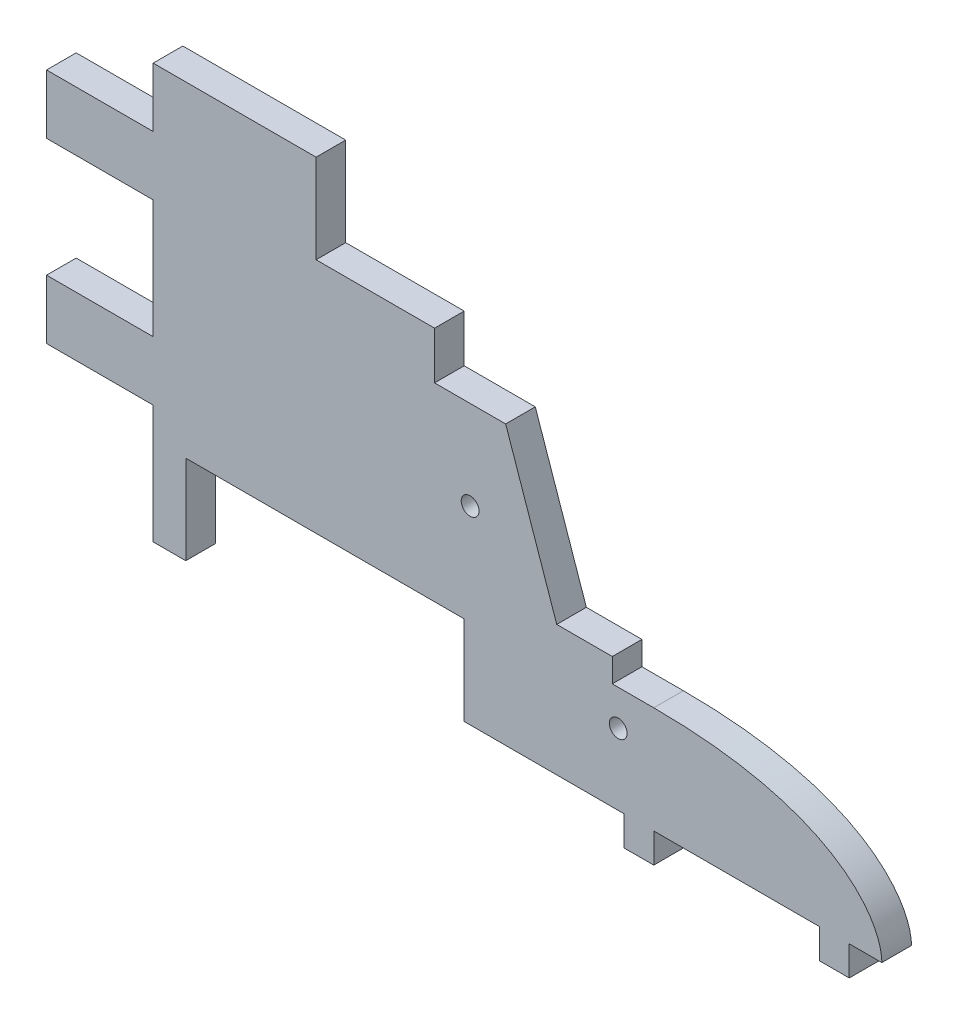
SolidWorks part; units mm, degrees
ref_plane "Plan de face" through (0, 0, 0) normal (0, 0, 1) x (1, 0, 0)
ref_plane "Plan de dessus" through (0, 0, 0) normal (0, 1, 0) x (1, 0, 0)
ref_plane "Plan de droite" through (0, 0, 0) normal (1, 0, 0) x (0, 0, -1)
sketch "Esquisse1" plane through (0, 0, 0) normal (0, 0, 1) x (1, 0, 0)
  line L1 (0, 0) -> (32, 0)
  line L2 (0, 0) -> (0, 47)
  line L3 (0, 47) -> (12, 47)
  line L4 (37, 0) -> (37, 18)
  line L6 (12, 47) -> (22, 18)
  line L7 (22, 18) -> (37, 18)
  line L8 (37, 0) -> (37, -5)
  line L9 (37, -5) -> (32, -5)
  line L10 (32, 0) -> (32, -5)
  circle A0 centre (6, 32) radius 1.5
  circle A1 centre (31, 12) radius 1.5
  dimension "D3" = 20
  dimension "D4" = 3
  dimension "D1" = 6
  dimension "D2" = 12
  dimension "D5" = 15
  dimension "D6" = 6
  dimension "D7" = 25
  dimension "D8" = 10
  dimension "D9" = 6
  dimension "D10" = 5
  dimension "D11" = 5
extrude "Boss.-Extru.1" add sketch "Esquisse1" along normal blind 5
sketch "Esquisse2" plane through (0, 0, 0) normal (0, 0, -1) x (-1, 0, 0)
  line L0 (-37, 18) -> (-22, 18) construction
  line L1 (-37, 0) -> (-65, 0)
  line L2 (-37, 0) -> (-37, 18)
  line L3 (-70, 0) -> (-75.5, 0)
  line L4 (42, 0) -> (47.5, 0)
  line L5 (0, 15) -> (0, 55)
  line L6 (0, 55) -> (20, 55)
  line L7 (47.5, 70) -> (47.5, 60)
  line L8 (0, 0) -> (-32, 0) construction
  line L9 (20, 55) -> (20, 70)
  line L10 (47.5, 50) -> (47.5, 30)
  line L11 (47.5, 20) -> (65.5, 20)
  line L13 (47.5, 30) -> (65.5, 30)
  line L14 (65.5, 20) -> (65.5, 30)
  line L15 (-70, 0) -> (-70, -5)
  line L16 (-70, -5) -> (-65, -5)
  line L17 (-65, 0) -> (-65, -5)
  line L18 (0, 15) -> (42, 15)
  line L19 (47.5, 60) -> (65.5, 60)
  line L20 (47.5, 20) -> (47.5, 0)
  line L21 (47.5, 50) -> (65.5, 50)
  line L22 (0, 47) -> (0, 0) construction
  line L23 (65.5, 60) -> (65.5, 50)
  line L26 (0, 0) -> (-32, 0) construction
  line L27 (42, 15) -> (42, 0)
  line L28 (-37, 18) -> (-22, 18) construction
  line L29 (-37, -5) -> (-37, 18) construction
  line L36 (-30, 18) -> (-22, 18)
  line L37 (-30, 18) -> (-30, 22)
  line L38 (-30, 22) -> (-20.6207, 22)
  line L39 (-22, 18) -> (-20.6207, 22)
  line L40 (-22, 18) -> (-12, 47) construction
  line L41 (20, 70) -> (47.5, 70)
  spline S0 degree 3 poles (-75.5, 0) (-75.5, 5.9822) (-67.6854, 18) (-37, 18) knots 0 0 0 0 1 1 1 1
  dimension "D1" = 38.5
  dimension "D2" = 20
  dimension "D3" = 28
  dimension "D4" = 47.5
  dimension "D5" = 10
  dimension "D6" = 18
  dimension "D7" = 20
  dimension "D8" = 20
  dimension "D9" = 15
  dimension "D12" = 5
  dimension "D13" = 42
  dimension "D14" = 15
  dimension "D15" = 40
  dimension "D22" = 4
  dimension "D23" = 8
extrude "Boss.-Extru.2" add sketch "Esquisse2" against normal blind 5
sketch "Esquisse4" plane through (0, 0, 0) normal (0, 0, -1) x (-1, 0, 0)
  line L0 (0, 0) -> (-32, 0) construction
  line L1 (0, 15) -> (-5, 15)
  line L2 (0, 15) -> (0, 0)
  line L3 (0, 0) -> (-5, 0)
  line L4 (-5, 15) -> (-5, 0)
  dimension "D1" = 5
extrude "Enlèv. mat.-Extru.1" cut sketch "Esquisse4" against normal blind 10
